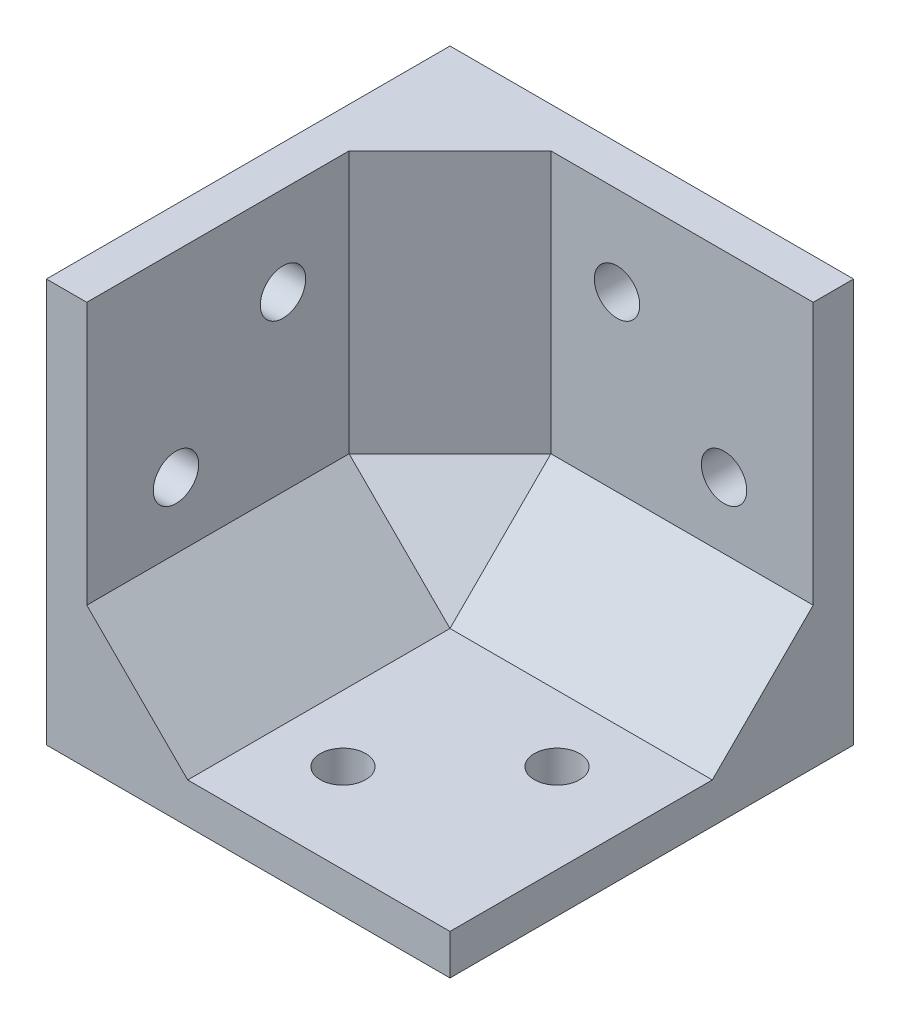
SolidWorks part; units mm, degrees
material "ABS"
ref_plane "Piano frontale" through (0, 0, 0) normal (0, 0, 1) x (1, 0, 0)
ref_plane "Piano superiore" through (0, 0, 0) normal (0, 1, 0) x (1, 0, 0)
ref_plane "Piano destro" through (0, 0, 0) normal (1, 0, 0) x (0, 0, -1)
sketch "Schizzo1" plane through (0, 0, 0) normal (0, 1, 0) x (1, 0, 0)
  line L1 (0, 0) -> (-40, 0)
  line L2 (0, 0) -> (0, 40)
  line L3 (0, 40) -> (-40, 40)
  line L4 (-40, 0) -> (-40, 40)
  dimension "D1" = 40
extrude "Estrusione-Estrusione1" add sketch "Schizzo1" along normal blind 4
sketch "Schizzo2" plane through (0, 4, 0) normal (0, 1, 0) x (1, 0, 0)
  line L0 (-36, 0) -> (-40, 0)
  line L1 (-40, 0) -> (0, 0) construction
  line L2 (-40, 0) -> (-40, 40)
  line L3 (-40, 40) -> (0, 40)
  line L4 (0, 40) -> (0, 36)
  line L5 (0, 0) -> (0, 40) construction
  line L6 (0, 36) -> (-36, 36)
  line L7 (-36, 36) -> (-36, 0)
  dimension "D1" = 4
extrude "Estrusione-Estrusione2" add sketch "Schizzo2" along normal blind 36
chamfer "Smusso1" distance 10 angle 45 3 edges at (-18, 4, -36) (-36, 4, -18) (-36, 22, -36)
hole_wizard "Foro per Vite M4-1" positions "Schizzo3" profile "Schizzo4" hole size "M4" standard "DIN"
sketch "Schizzo3" plane through (0, 0, 0) normal (0, -1, 0) x (-1, 0, 0)
  line L0 (0, 0) -> (40, 40) construction
  line L2 (0, 10.6066) -> (29.3934, 40) construction
  line L3 (0, 0) -> (0, 40) construction
  line L4 (0, 40) -> (40, 40) construction
  line L6 (10.6066, 0) -> (40, 29.3934) construction
  line L7 (40, 0) -> (0, 0) construction
  line L8 (40, 40) -> (40, 0) construction
  line L10 (8.8388, 19.4454) -> (19.4454, 8.8388) construction
  point P0 (8.8388, 19.4454)
  point P2 (19.4454, 8.8388)
  dimension "D1" = 7.5
  dimension "D2" = 7.5
  dimension "D3" = 20
sketch "Schizzo4" plane through (-8.8388, 0, -19.4454) normal (1, 0, 0) x (0, 0, -1)
  line L0 (0, 0) -> (0, 10.3519)
  line L1 (0, 10.3519) -> (2.25, 9)
  line L2 (2.25, 9) -> (2.25, 0)
  line L5 (2.25, 0) -> (0, 0)
  line L10 (0, 10.3519) -> (-2.25, 9) construction
  line L11 (0, -6.35) -> (0, 107.95) construction
  dimension "Hole Dia." = 4.5
  dimension "Hole Depth" = 9
  dimension "Drill Angle" = 118
sketch "Schizzo5" plane through (0, 0, -40) normal (0, 0, -1) x (-1, 0, 0)
  line L0 (0, 40) -> (40, 0) construction
  line L2 (0, 29.3934) -> (29.3934, 0) construction
  line L3 (0, 40) -> (0, 0) construction
  line L4 (0, 0) -> (40, 0) construction
  line L6 (40, 10.6066) -> (10.6066, 40) construction
  line L7 (40, 40) -> (40, 0) construction
  line L8 (0, 40) -> (40, 40) construction
  line L10 (8.8388, 20.5546) -> (19.4454, 31.1612) construction
  point P0 (8.8388, 20.5546)
  point P2 (19.4454, 31.1612)
  dimension "D1" = 7.5
  dimension "D2" = 7.5
  dimension "D3" = 20
hole_wizard "Foro per Vite M4-2" positions "Schizzo5" profile "Schizzo6" hole size "M4" standard "DIN"
sketch "Schizzo6" plane through (-8.8388, 20.5546, -40) normal (1, 0, 0) x (0, 1, 0)
  line L0 (0, 0) -> (0, 10.3519)
  line L1 (0, 10.3519) -> (2.25, 9)
  line L2 (2.25, 9) -> (2.25, 0)
  line L5 (2.25, 0) -> (0, 0)
  line L10 (0, 10.3519) -> (-2.25, 9) construction
  line L11 (0, -6.35) -> (0, 107.95) construction
  dimension "Hole Dia." = 4.5
  dimension "Hole Depth" = 9
  dimension "Drill Angle" = 118
hole_wizard "Foro per Vite M4-3" positions "Schizzo7" profile "Schizzo8" hole size "M4" standard "DIN"
sketch "Schizzo7" plane through (-40, 0, 0) normal (-1, 0, 0) x (0, 0, 1)
  line L0 (-40, 0) -> (0, 40) construction
  line L2 (-10.6066, 40) -> (-40, 10.6066) construction
  line L3 (-40, 40) -> (0, 40) construction
  line L4 (-40, 40) -> (-40, 0) construction
  line L6 (0, 29.3934) -> (-29.3934, 0) construction
  line L7 (0, 40) -> (0, 0) construction
  line L8 (-40, 0) -> (0, 0) construction
  line L10 (-19.4454, 31.1612) -> (-8.8388, 20.5546) construction
  point P0 (-19.4454, 31.1612)
  point P2 (-8.8388, 20.5546)
  dimension "D1" = 7.5
  dimension "D2" = 7.5
  dimension "D3" = 20
sketch "Schizzo8" plane through (-40, 31.1612, -19.4454) normal (0, 1, 0) x (0, 0, 1)
  line L0 (0, 0) -> (0, 10.3519)
  line L1 (0, 10.3519) -> (2.25, 9)
  line L2 (2.25, 9) -> (2.25, 0)
  line L5 (2.25, 0) -> (0, 0)
  line L10 (0, 10.3519) -> (-2.25, 9) construction
  line L11 (0, -6.35) -> (0, 107.95) construction
  dimension "Hole Dia." = 4.5
  dimension "Hole Depth" = 9
  dimension "Drill Angle" = 118
